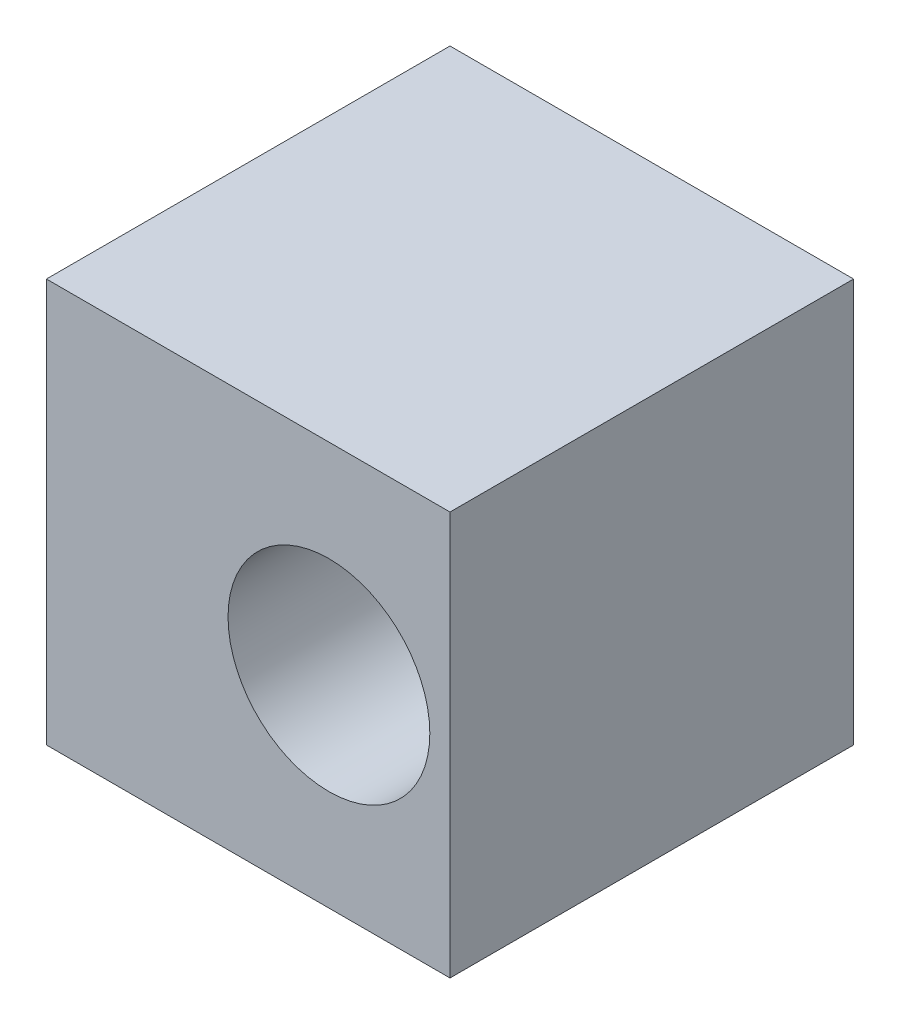
SolidWorks part; units mm, degrees
ref_plane "Front Plane" through (0, 0, 0) normal (0, 0, 1) x (1, 0, 0)
ref_plane "Top Plane" through (0, 0, 0) normal (0, 1, 0) x (1, 0, 0)
ref_plane "Right Plane" through (0, 0, 0) normal (1, 0, 0) x (0, 0, -1)
sketch "Sketch1" plane through (0, 0, 0) normal (0, 0, 1) x (1, 0, 0)
  line L1 (0, 0) -> (10, 0)
  line L2 (0, 0) -> (0, 10)
  line L3 (0, 10) -> (10, 10)
  line L4 (10, 0) -> (10, 10)
extrude "Boss-Extrude1" add sketch "Sketch1" along normal blind 10
sketch "Sketch2" plane through (0, 0, 0) normal (0, 0, 1) x (1, 0, 0)
  circle A0 centre (7, 5) radius 2.5
extrude "Cut-Extrude2" cut sketch "Sketch2" along normal through all
